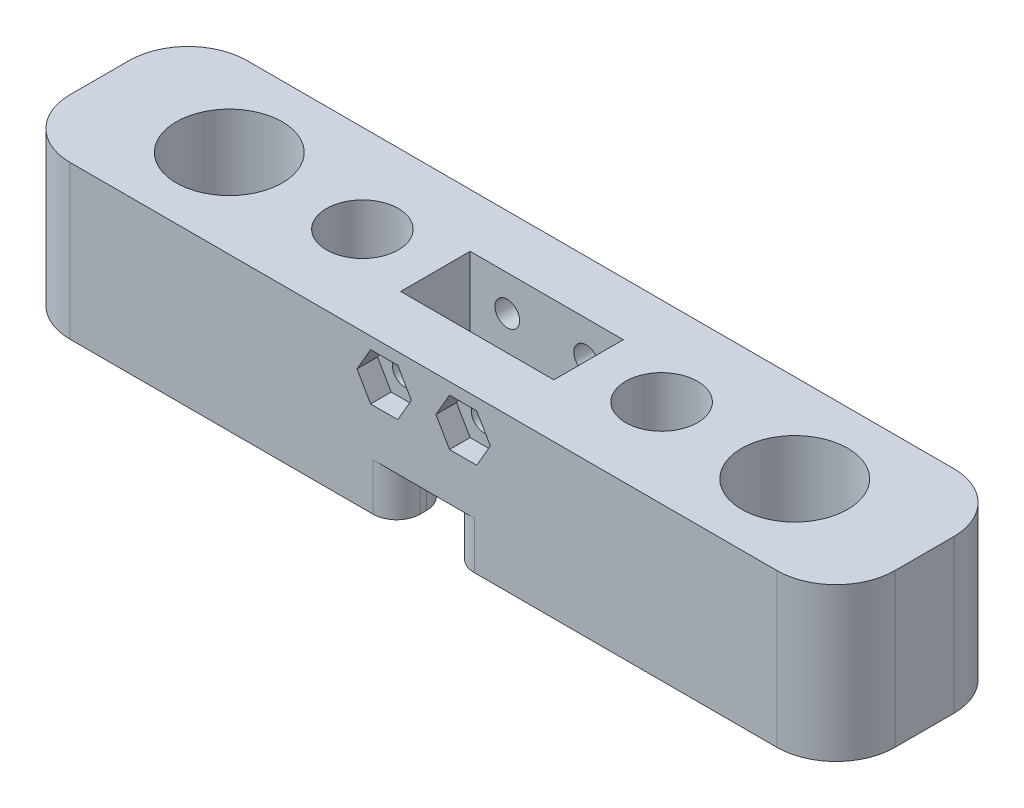
SolidWorks part; units mm, degrees
ref_plane "Front Plane" through (0, 0, 0) normal (0, 0, 1) x (1, 0, 0)
ref_plane "Top Plane" through (0, 0, 0) normal (0, 1, 0) x (1, 0, 0)
ref_plane "Right Plane" through (0, 0, 0) normal (1, 0, 0) x (0, 0, -1)
sketch "Sketch1" plane through (0, 0, 0) normal (0, 0, 1) x (1, 0, 0)
  line L1 (0, 0) -> (40, 0)
  line L2 (0, 0) -> (0, 13)
  line L3 (0, 13) -> (40, 13)
  line L4 (40, 0) -> (40, 13)
  dimension "D1" = 40
  dimension "D2" = 13
extrude "SwitchCase" add sketch "Sketch1" along normal blind 15
sketch "Sketch2" plane through (0, 13, 0) normal (0, 1, 0) x (1, 0, 0)
  line L1 (13.5, -4.55) -> (26.5, -4.55)
  line L2 (13.5, -4.55) -> (13.5, -10.45)
  line L3 (13.5, -10.45) -> (26.5, -10.45)
  line L4 (26.5, -4.55) -> (26.5, -10.45)
  line L5 (40, 0) -> (0, 0) construction
  point P4 (20, 0)
  point P5 (20, -4.55)
  point P9 (13.5, -7.5)
  dimension "D1" = 5.9
  dimension "D2" = 13
  dimension "D4" = 7.5
extrude "SwitchCavity" cut sketch "Sketch2" against normal through all
sketch "Sketch3" plane through (0, 0, 4.55) normal (0, 0, 1) x (1, 0, 0)
  line L0 (13.5, 0) -> (13.5, 13) construction
  line L1 (26.5, 0) -> (26.5, 13) construction
  line L3 (40, 13) -> (0, 13) construction
  line L4 (26.5, 13) -> (13.5, 13) construction
  circle A0 centre (16.65, 10) radius 1.05
  circle A1 centre (23.35, 10) radius 1.05
  dimension "D1" = 2.1
  dimension "D2" = 3.15
  dimension "D3" = 3.15
  dimension "D4" = 3
  dimension "D5" = 3
extrude "SwitchM2Holes" cut sketch "Sketch3" against normal through all both and the other way through all
sketch "Sketch14" plane through (0, 0, 0) normal (0, 0, -1) x (-1, 0, 0)
  line L0 (-20, 13) -> (-20, -0.8547) construction
  line L3 (-40, 13) -> (0, 13) construction
  circle A0 centre (-23.35, 10) radius 2
  circle A2 centre (-16.65, 10) radius 2
  dimension "D1" = 4
extrude "M2Head" cut sketch "Sketch14" against normal blind 1.5
sketch "Sketch5" plane through (0, 0, 15) normal (0, 0, 1) x (1, 0, 0)
  line L1 (18.9594, 10) -> (17.8047, 12)
  line L2 (17.8047, 12) -> (15.4953, 12)
  line L3 (15.4953, 12) -> (14.3406, 10)
  line L4 (14.3406, 10) -> (15.4953, 8)
  line L5 (15.4953, 8) -> (17.8047, 8)
  line L6 (17.8047, 8) -> (18.9594, 10)
  line L8 (25.6594, 10) -> (24.5047, 12)
  line L9 (24.5047, 12) -> (22.1953, 12)
  line L10 (22.1953, 12) -> (21.0406, 10)
  line L11 (21.0406, 10) -> (22.1953, 8)
  line L12 (22.1953, 8) -> (24.5047, 8)
  line L13 (24.5047, 8) -> (25.6594, 10)
  circle A0 centre (16.65, 10) radius 2 construction
  circle A1 centre (23.35, 10) radius 2 construction
  dimension "D1" = 4
  dimension "D2" = 2
extrude "M2NutInserts" cut sketch "Sketch5" against normal blind 1.75 and the other way through all
sketch "Sketch7" plane through (0, 0, 15) normal (0, 0, 1) x (1, 0, 0)
  line L0 (0, 13) -> (-15, 13)
  line L2 (0, 0) -> (0, 13)
  line L3 (40, 13) -> (55, 13)
  line L5 (40, 0) -> (40, 13)
  line L6 (0, 0) -> (-15, 0)
  line L7 (-15, 0) -> (-15, 13)
  line L8 (40, 0) -> (55, 0)
  line L9 (55, 0) -> (55, 13)
  point P5 (0, 0)
  point P8 (0, 0)
  dimension "D1" = 15
  dimension "D2" = 13
extrude "Wings" add sketch "Sketch7" against normal up to surface (15 mm away) up to face at (21.35, 10, 0)
sketch "Sketch9" plane through (0, 0, 0) normal (0, -1, 0) x (1, 0, 0)
  line L1 (37.2322, 7.5) -> (34.9661, 11.425)
  line L2 (34.9661, 11.425) -> (30.4339, 11.425)
  line L3 (30.4339, 11.425) -> (28.1678, 7.5)
  line L4 (28.1678, 7.5) -> (30.4339, 3.575)
  line L5 (30.4339, 3.575) -> (34.9661, 3.575)
  line L6 (34.9661, 3.575) -> (37.2322, 7.5)
  line L9 (26.5, 10.45) -> (26.5, 4.55) construction
  line L10 (20, 10.45) -> (20, 4.55) construction
  line L11 (13.5, 10.45) -> (26.5, 10.45) construction
  line L12 (26.5, 4.55) -> (13.5, 4.55) construction
  line L19 (5.0339, 3.575) -> (2.7678, 7.5)
  line L20 (9.5661, 3.575) -> (5.0339, 3.575)
  line L21 (11.8322, 7.5) -> (9.5661, 3.575)
  line L22 (9.5661, 11.425) -> (11.8322, 7.5)
  line L23 (5.0339, 11.425) -> (9.5661, 11.425)
  line L24 (2.7678, 7.5) -> (5.0339, 11.425)
  circle A0 centre (32.7, 7.5) radius 3.925 construction
  point P26 (26.5, 7.5)
  dimension "D2" = 3.925
  dimension "D1" = 7.85
  dimension "D3" = 12.7
extrude "M5Nuts" cut sketch "Sketch9" against normal blind 4
sketch "Sketch10" plane through (0, 0, 0) normal (0, -1, 0) x (1, 0, 0)
  line L1 (9.5661, 11.425) -> (5.0339, 11.425) construction
  line L2 (20, 10.45) -> (20, 4.55) construction
  line L3 (13.5, 10.45) -> (26.5, 10.45) construction
  line L4 (26.5, 4.55) -> (13.5, 4.55) construction
  circle A0 centre (7.3, 7.5) radius 3.05
  circle A3 centre (32.7, 7.5) radius 3.05
  point P7 (7.3, 11.425)
  dimension "D1" = 6.1
extrude "M6Hole" cut sketch "Sketch10" against normal through all
sketch "Sketch11" plane through (0, 0, 4.55) normal (0, 0, 1) x (1, 0, 0)
  line L1 (22.3, 4) -> (17.7, 4)
  line L2 (22.3, 4) -> (22.3, 0)
  line L3 (22.3, 0) -> (17.7, 0)
  line L4 (17.7, 4) -> (17.7, 0)
  line L6 (26.5, 0) -> (13.5, 0) construction
  circle A1 centre (16.65, 10) radius 1.05 construction
  point P4 (20, 0)
  point P5 (20, 0)
  dimension "D1" = 4
extrude "WireChannel" cut sketch "Sketch11" against normal through all both and the other way through all
fillet "ChannelFillet" radius 2 10 edges at (17.7, 2, 4.55) (17.7, 2, 0) (17.7, 2, 15) (17.7, 2, 10.45) (20, 4, 10.45) (20, 4, 4.55) (22.3, 2, 0) (22.3, 2, 4.55) (22.3, 2, 15) (22.3, 2, 10.45)
sketch "Sketch12" plane through (0, 13, 0) normal (0, 1, 0) x (1, 0, 0)
  line L0 (26.5, -4.55) -> (13.5, -4.55) construction
  line L1 (26.5, -10.45) -> (26.5, -4.55) construction
  line L2 (20, -4.55) -> (20, -10.45) construction
  line L3 (13.5, -10.45) -> (26.5, -10.45) construction
  circle A0 centre (44, -7.5) radius 4.5
  circle A1 centre (-4, -7.5) radius 4.5
  point P4 (20, -4.55)
  point P7 (26.5, -7.5)
  dimension "D1" = 9
  dimension "D2" = 24
extrude "M5Head" cut sketch "Sketch12" against normal blind 8 and the other way through all
sketch "Sketch13" plane through (0, 13, 0) normal (0, 1, 0) x (1, 0, 0)
  line L0 (20, -4.55) -> (20, -10.45) construction
  line L1 (26.5, -4.55) -> (13.5, -4.55) construction
  line L2 (13.5, -10.45) -> (26.5, -10.45) construction
  circle A0 centre (44, -7.5) radius 2.75
  circle A1 centre (-4, -7.5) radius 2.75
  dimension "D1" = 5.5
extrude "M5Thread" cut sketch "Sketch13" against normal through all
fillet "EndFillet" radius 5 4 edges at (-15, 6.5, 15) (-15, 6.5, 0) (55, 6.5, 15) (55, 6.5, 0)
